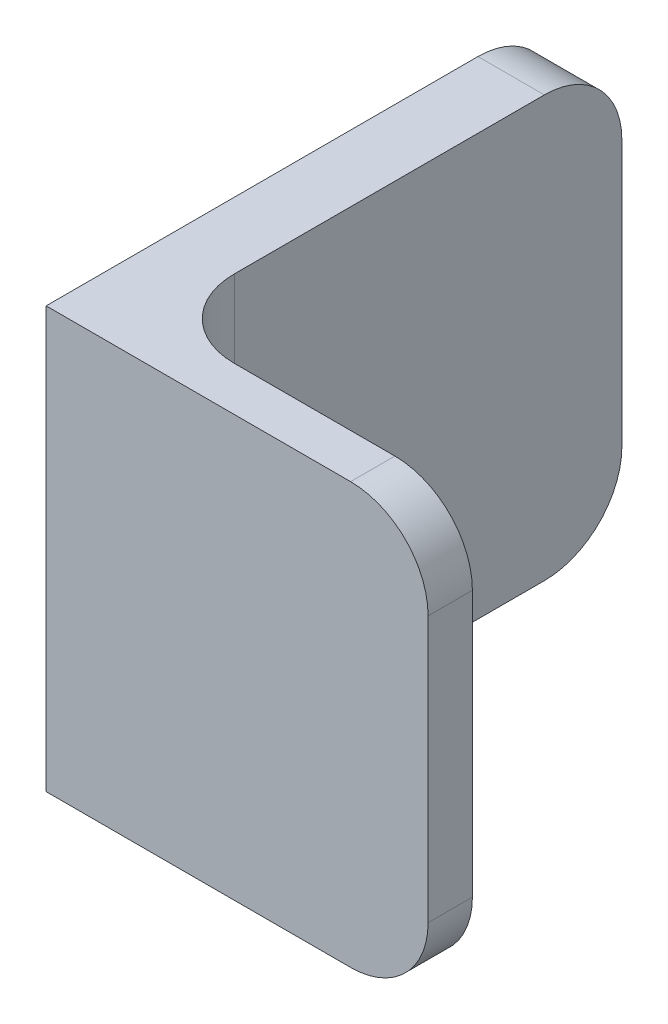
SolidWorks part; units mm, degrees
ref_plane "Front Plane" through (0, 0, 0) normal (0, 0, 1) x (1, 0, 0)
ref_plane "Top Plane" through (0, 0, 0) normal (0, 1, 0) x (1, 0, 0)
ref_plane "Right Plane" through (0, 0, 0) normal (1, 0, 0) x (0, 0, -1)
sketch "Sketch1" plane through (0, 0, 0) normal (0, 1, 0) x (1, 0, 0)
  line L0 (0, 0) -> (0, 46)
  line L1 (0, 46) -> (6, 46)
  line L2 (6, 46) -> (6, 4)
  line L3 (6, 4) -> (34.5, 4)
  line L4 (34.5, 4) -> (34.5, 0)
  line L5 (34.5, 0) -> (0, 0)
  dimension "D1" = 46
  dimension "D2" = 34.5
  dimension "D3" = 4
  dimension "D4" = 6
extrude "Boss-Extrude1" add sketch "Sketch1" along normal blind 38
fillet "Fillet2" radius 7 5 edges at (3, 0, -46) (3, 38, -46) (34.5, 0, -2) (6, 19, -4) (34.5, 38, -2)
